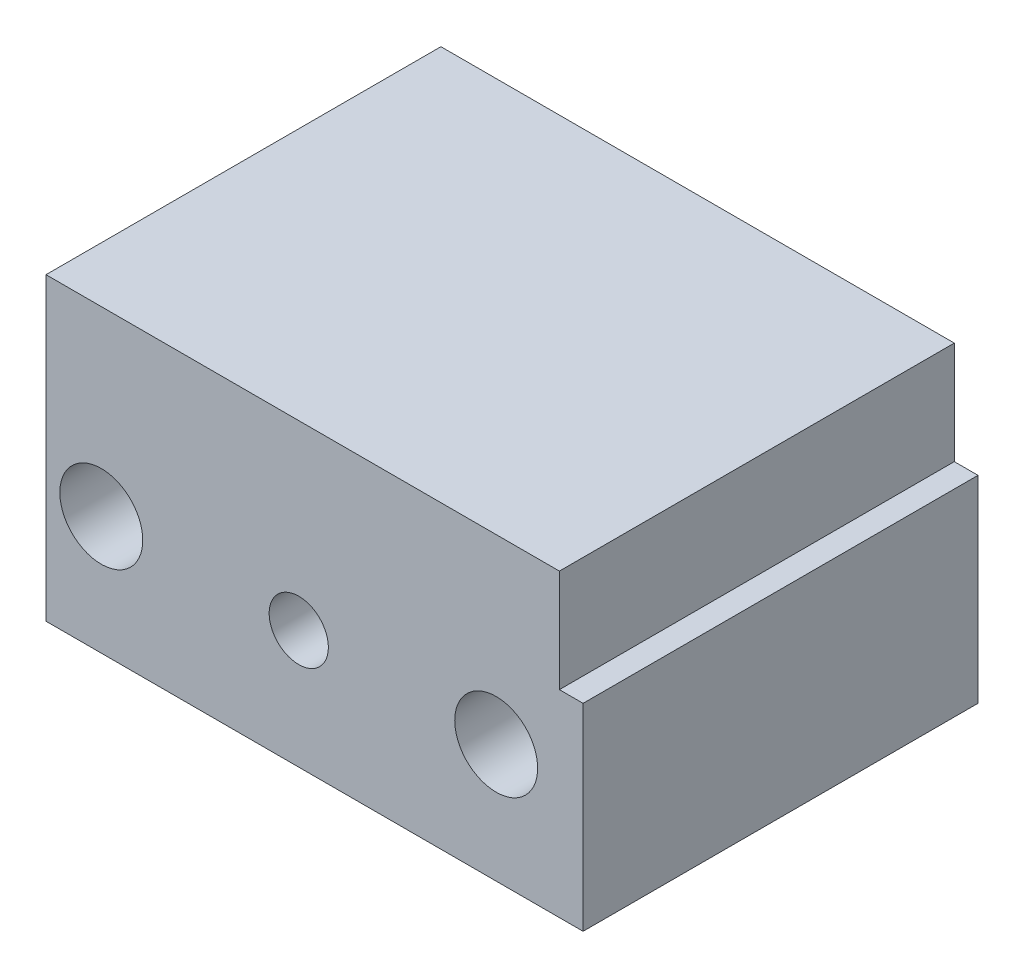
SolidWorks part; units mm, degrees
material "Polyetheretherketone (PEEK)"
ref_plane "Front Plane" through (0, 0, 0) normal (0, 0, 1) x (1, 0, 0)
ref_plane "Top Plane" through (0, 0, 0) normal (0, 1, 0) x (1, 0, 0)
ref_plane "Right Plane" through (0, 0, 0) normal (1, 0, 0) x (0, 0, -1)
ref_plane "Plane1" through (0, 4, 0) normal (0, 1, 0) x (-1, 0, 0)
sketch "Sketch1" plane through (0, 4, 0) normal (0, 1, 0) x (-1, 0, 0)
  line L0 (0, 0) -> (0, 5)
  line L1 (0, 5) -> (-6.8, 5)
  line L2 (-6.8, 5) -> (-6.8, 0)
  line L3 (-6.8, 0) -> (0, 0)
  dimension "D1" = 5
  dimension "D2" = 6.8
extrude "Boss-Extrude1" add sketch "Sketch1" against normal blind 3.8
hole_wizard "Hole1" positions "Sketch7" profile "Sketch6" legacy end condition through all
sketch "Sketch7" plane through (0, 0, 0) normal (0, 0, -1) x (-1, 0, 0)
  point P0 (-5.7, 1.7)
  point P1 (-0.7, 1.7)
  dimension "D1" = 5
  dimension "D2" = 1.5
  dimension "D3" = 0.7
  dimension "D4" = 5.7
sketch "Sketch6" plane through (5.7, 1.7, 0) normal (1, 0, 0) x (0, 1, 0)
  line L0 (0, 0) -> (0, 5)
  line L1 (0, 5) -> (0.525, 5)
  line L2 (0.525, 5) -> (0.525, 1.2)
  line L3 (0.525, 1.2) -> (0.65, 1.2)
  line L4 (0.65, 1.2) -> (0.65, 0)
  line L5 (0.65, 0) -> (0, 0)
  line L6 (0, 110) -> (0, -10) construction
  dimension "Diameter" = 1.05
  dimension "Depth" = 5
  dimension "C-Bore Diameter" = 1.3
  dimension "C-Bore Depth" = 1.2
sketch "Sketch20" plane through (6.8, 0, 0) normal (1, 0, 0) x (0, 0, -1)
  line L0 (0, 2.225) -> (0, 4) construction
  line L1 (-5, 4) -> (0, 4)
  line L2 (-5, 4) -> (-5, 2.7)
  line L3 (-5, 2.7) -> (0, 2.7)
  line L4 (0, 4) -> (0, 2.7)
  dimension "D1" = 1.3
extrude "Cut-Extrude11" cut sketch "Sketch20" against normal blind 0.3
sketch "Sketch22" plane through (0, 0, 0) normal (0, 0, -1) x (-1, 0, 0)
  line L0 (-6.8, 0.2) -> (0, 0.2) construction
  line L1 (-6.8, 0.2) -> (-6.8, 2.7) construction
  line L3 (-5.6, 2.35) -> (-6.8, 2.35)
  line L4 (-5.6, 2.35) -> (-5.6, 1.05)
  line L5 (-5.6, 1.05) -> (-6.8, 1.05)
  line L6 (-6.8, 2.35) -> (-6.8, 1.05)
  circle A0 centre (-5.6, 1.7) radius 0.65
  dimension "D1" = 1.3
  dimension "D2" = 1.5
  dimension "D3" = 1.2
extrude "Cut-Extrude12" [suppressed] cut sketch "Sketch22" against normal blind 1.2
hole_wizard "M1.0x0.25 Tapped Hole1" positions "Sketch32" profile "Sketch34" tap size "M1.0x0.25" standard "ANSI Metric" end condition up to next
sketch "Sketch32" plane through (0, 0, 0) normal (0, 0, -1) x (-1, 0, 0)
  line L0 (-5.7, 1.7) -> (-0.7, 1.7) construction
  circle A0 centre (-0.7, 1.7) radius 0.65 construction
  circle A1 centre (-0.7, 1.7) radius 0.65
  circle A4 centre (-5.7, 1.7) radius 0.65 construction
  circle A5 centre (-5.7, 1.7) radius 0.65
  point P20 (-3.2, 1.7)
cosmetic thread "Hole Thread4"
sketch "Sketch34" plane through (3.2, 1.7, 0) normal (1, 0, 0) x (0, 1, 0)
  line L0 (0, 0) -> (0, 5)
  line L1 (0, 5) -> (0.375, 5)
  line L2 (0.375, 5) -> (0.375, 0)
  line L5 (0.375, 0) -> (0, 0)
  line L11 (0, -6.35) -> (0, 107.95) construction
  dimension "Thru Tap Drill Dia." = 0.75
  dimension "Thru Tap Drill Depth" = 5
